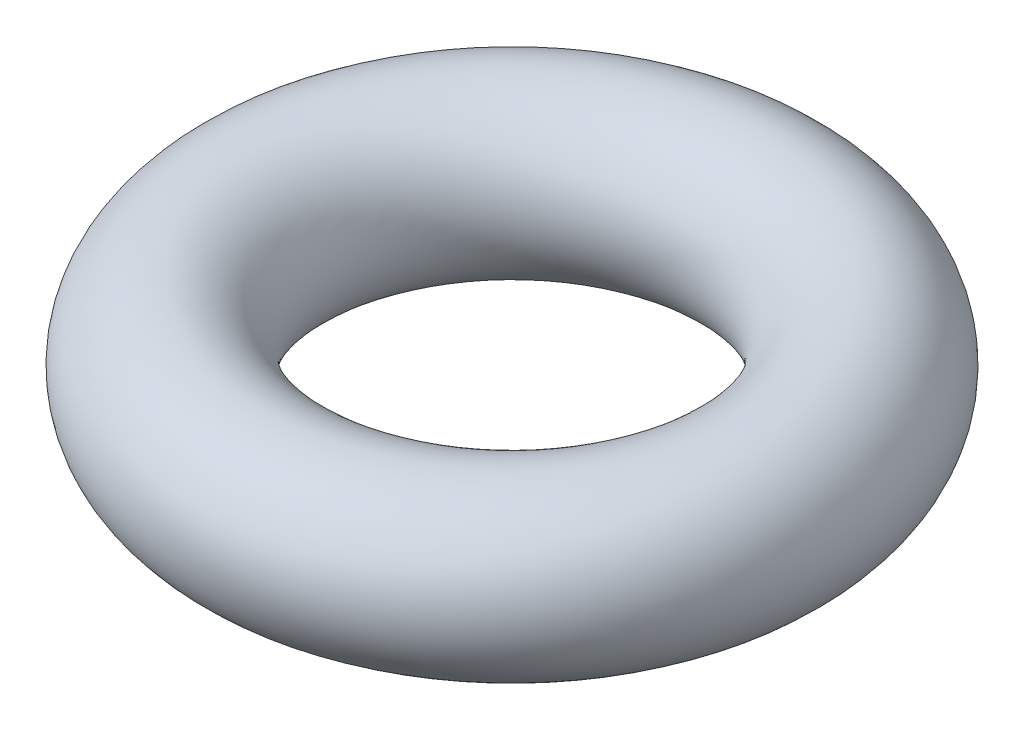
SolidWorks part; units mm, degrees
material "Rubber"
ref_plane "Front Plane" through (0, 0, 0) normal (0, 0, 1) x (1, 0, 0)
ref_plane "Top Plane" through (0, 0, 0) normal (0, 1, 0) x (1, 0, 0)
ref_plane "Right Plane" through (0, 0, 0) normal (1, 0, 0) x (0, 0, -1)
sketch "Sketch1" plane through (0, 0, 0) normal (0, 0, 1) x (1, 0, 0)
  line L0 (0, 0) -> (3, 0) construction
  line L1 (0, 2.3178) -> (0, -1.7944) construction
  circle A0 centre (3, 0) radius 1
  point P4 (4, 0)
  point P5 (2, 0)
  point P7 (0.6206, 0)
  dimension "D1" = 4
  dimension "D2" = 2
revolve "Revolve1" add sketch "Sketch1" angle 360 about L1
